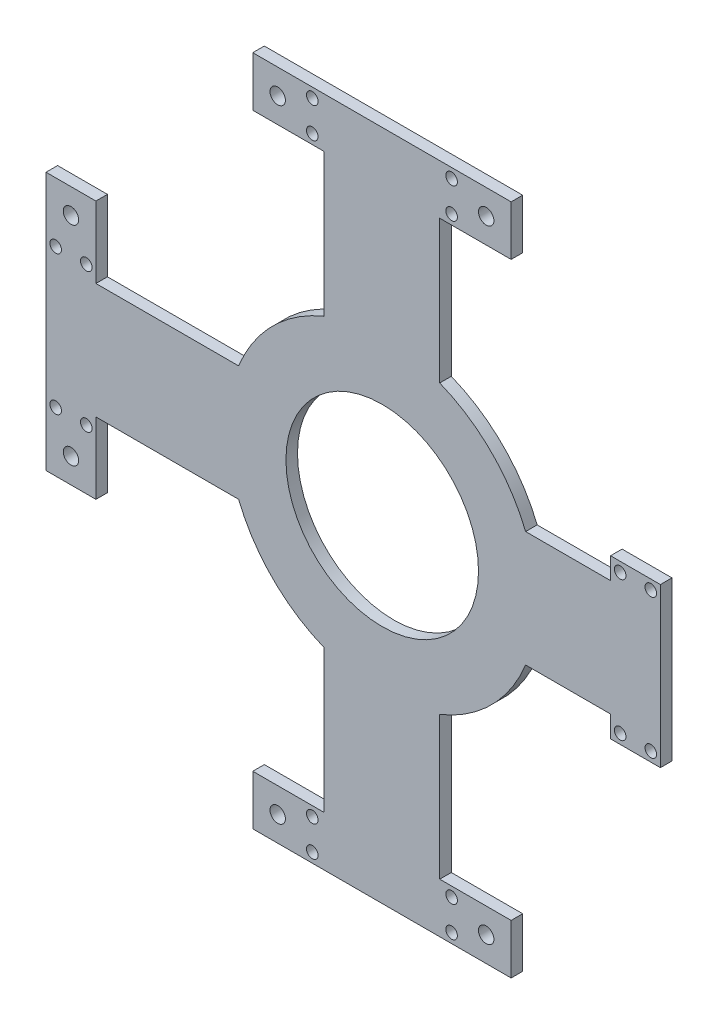
SolidWorks part; units mm, degrees
ref_plane "Alzado" through (0, 0, 0) normal (0, 0, 1) x (1, 0, 0)
ref_plane "Planta" through (0, 0, 0) normal (0, 1, 0) x (1, 0, 0)
ref_plane "Vista lateral" through (0, 0, 0) normal (1, 0, 0) x (0, 0, -1)
sketch "Croquis1" plane through (0, 0, 0) normal (0, 0, 1) x (1, 0, 0)
  line L0 (0, 0) -> (0, 37.2565) construction
  line L1 (-15.071, 74.3065) -> (-15.071, 37.2565)
  line L2 (-37.2851, 15) -> (-74.3351, 15)
  line L3 (-15.071, 37.2565) -> (14.929, 37.2565) construction
  line L4 (14.929, 37.2565) -> (14.929, 74.3065)
  line L5 (-15.071, 74.3065) -> (-20.661, 74.3065)
  line L6 (-25, 0) -> (25, 0) construction
  line L7 (0, 25) -> (0, -25) construction
  line L8 (-15.071, -37.2565) -> (-15.071, -74.3065)
  line L9 (14.929, -37.2565) -> (14.929, -74.3065)
  line L10 (14.929, 74.3065) -> (20.519, 74.3065)
  line L12 (-37.2851, -15) -> (-74.3351, -15)
  line L13 (-20.661, 74.3065) -> (-20.661, 87.2565)
  line L14 (-20.661, 87.2565) -> (20.519, 87.2565)
  line L15 (20.519, 87.2565) -> (20.519, 74.3065)
  line L16 (20.519, -87.2565) -> (20.519, -74.3065)
  line L17 (14.929, -74.3065) -> (20.519, -74.3065)
  line L18 (-20.661, -87.2565) -> (20.519, -87.2565)
  line L19 (-20.661, -74.3065) -> (-20.661, -87.2565)
  line L20 (-15.071, -74.3065) -> (-20.661, -74.3065)
  line L21 (-74.3351, -15) -> (-74.3351, -20.59)
  line L22 (-74.3351, -20.59) -> (-87.2851, -20.59)
  line L23 (-87.2851, -20.59) -> (-87.2851, 20.59)
  line L24 (-87.2851, 20.59) -> (-74.3351, 20.59)
  line L25 (-74.3351, 20.59) -> (-74.3351, 15)
  line L26 (37.228, 15) -> (59.278, 15)
  line L27 (37.228, -15) -> (59.278, -15)
  line L28 (59.278, -15) -> (59.278, -20.59)
  line L29 (59.278, -20.59) -> (72.228, -20.59)
  line L30 (72.228, -20.59) -> (72.228, 20.59)
  line L31 (72.228, 20.59) -> (59.278, 20.59)
  line L32 (59.278, 20.59) -> (59.278, 15)
  arc A0 (-15.071, 37.2565) -> (-37.2851, 15) centre (0, 0) ccw
  circle A1 centre (0, 0) radius 25
  arc A2 (-37.2851, -15) -> (-15.071, -37.2565) centre (0, 0) ccw
  arc A3 (14.929, 37.2565) -> (37.228, 15) centre (0, 0) cw
  arc A4 (14.929, -37.2565) -> (37.228, -15) centre (0, 0) ccw
  dimension "D1" = 50
  dimension "D2" = 5.59
  dimension "D3" = 37.05
  dimension "D4" = 5.59
  dimension "D5" = 12.95
  dimension "D6" = 37.05
  dimension "D7" = 37.05
  dimension "D8" = 5.59
  dimension "D9" = 5.59
  dimension "D10" = 12.95
  dimension "D11" = 37.05
  dimension "D12" = 37.05
  dimension "D13" = 22.05
  dimension "D14" = 5.59
  dimension "D15" = 22.05
  dimension "D16" = 5.59
  dimension "D17" = 12.95
  dimension "D18" = 12.95
  dimension "D19" = 30
  dimension "D20" = 12.95
  dimension "D21" = 41.18
extrude "Saliente-Extruir1" add sketch "Croquis1" along normal blind 3
sketch "Croquis2" plane through (0, 0, 0) normal (0, 0, -1) x (-1, 0, 0)
  line L1 (-20.519, 87.2565) -> (-33.469, 87.2565)
  line L2 (-20.519, 87.2565) -> (-20.519, 74.3065)
  line L3 (-20.519, 74.3065) -> (-33.469, 74.3065)
  line L4 (-33.469, 87.2565) -> (-33.469, 74.3065)
  line L5 (20.661, 87.2565) -> (33.611, 87.2565)
  line L6 (20.661, 87.2565) -> (20.661, 74.3065)
  line L7 (20.661, 74.3065) -> (33.611, 74.3065)
  line L8 (33.611, 87.2565) -> (33.611, 74.3065)
  line L9 (-20.519, -74.3065) -> (-33.469, -74.3065)
  line L10 (-20.519, -74.3065) -> (-20.519, -87.2565)
  line L11 (-20.519, -87.2565) -> (-33.469, -87.2565)
  line L12 (-33.469, -74.3065) -> (-33.469, -87.2565)
  line L13 (20.661, -74.3065) -> (33.611, -74.3065)
  line L14 (20.661, -74.3065) -> (20.661, -87.2565)
  line L15 (20.661, -87.2565) -> (33.611, -87.2565)
  line L16 (33.611, -74.3065) -> (33.611, -87.2565)
  line L17 (74.3351, 20.59) -> (87.2851, 20.59)
  line L18 (74.3351, 20.59) -> (74.3351, 33.54)
  line L19 (74.3351, 33.54) -> (87.2851, 33.54)
  line L20 (87.2851, 20.59) -> (87.2851, 33.54)
  line L21 (74.3351, -20.59) -> (87.2851, -20.59)
  line L22 (74.3351, -20.59) -> (74.3351, -33.54)
  line L23 (74.3351, -33.54) -> (87.2851, -33.54)
  line L24 (87.2851, -20.59) -> (87.2851, -33.54)
  dimension "D1" = 12.95
  dimension "D2" = 12.95
  dimension "D3" = 12.95
  dimension "D4" = 12.95
  dimension "D5" = 12.95
  dimension "D6" = 12.95
  dimension "D7" = 12.95
  dimension "D8" = 12.95
  dimension "D9" = 12.95
  dimension "D10" = 12.95
  dimension "D11" = 12.95
extrude "Saliente-Extruir2" add sketch "Croquis2" against normal blind 3
sketch "Croquis3" plane through (0, 0, 0) normal (0, 0, -1) x (-1, 0, 0)
  line L0 (-33.469, 74.3065) -> (-20.519, 74.3065) construction
  line L1 (-14.929, 74.3065) -> (-33.469, 74.3065) construction
  line L2 (-33.469, 74.3065) -> (-20.519, 87.2565) construction
  line L3 (33.611, 87.2565) -> (-33.469, 87.2565) construction
  line L4 (-20.519, -74.3065) -> (-20.519, -87.2565) construction
  line L5 (-14.929, -74.3065) -> (-33.469, -74.3065) construction
  line L6 (33.611, -87.2565) -> (-33.469, -87.2565) construction
  line L7 (33.611, 87.2565) -> (20.661, 87.2565) construction
  line L8 (20.661, 87.2565) -> (20.661, 74.3065) construction
  line L9 (15.071, 74.3065) -> (33.611, 74.3065) construction
  line L10 (33.611, -74.3065) -> (20.661, -74.3065) construction
  line L12 (-33.469, -74.3065) -> (-20.519, -87.2565) construction
  line L13 (15.071, -74.3065) -> (33.611, -74.3065) construction
  line L14 (20.661, 74.3065) -> (33.611, 74.3065) construction
  line L15 (33.611, 74.3065) -> (20.661, 87.2565) construction
  line L16 (87.2851, -33.54) -> (87.2851, -20.59) construction
  line L17 (87.2851, -33.54) -> (87.2851, 33.54) construction
  line L18 (87.2851, -20.59) -> (74.3351, -20.59) construction
  line L19 (74.3351, -15) -> (74.3351, -33.54) construction
  line L20 (87.2851, 33.54) -> (87.2851, 20.59) construction
  line L21 (87.2851, 20.59) -> (74.3351, 20.59) construction
  line L22 (74.3351, 33.54) -> (74.3351, 15) construction
  line L23 (87.2851, 20.59) -> (74.3351, 33.54) construction
  line L24 (74.3351, -33.54) -> (87.2851, -20.59) construction
  line L26 (-20.519, -74.3065) -> (-33.469, -74.3065) construction
  line L27 (-33.469, 87.2565) -> (-33.469, 74.3065) construction
  line L28 (33.611, 74.3065) -> (33.611, 87.2565) construction
  line L29 (87.2851, 33.54) -> (74.3351, 33.54) construction
  line L30 (74.3351, -33.54) -> (87.2851, -33.54) construction
  line L32 (-33.469, -74.3065) -> (-33.469, -87.2565) construction
  line L33 (20.661, -74.3065) -> (20.661, -87.2565) construction
  line L34 (20.661, -87.2565) -> (33.611, -74.3065) construction
  line L35 (33.611, -87.2565) -> (33.611, -74.3065) construction
  circle A0 centre (-26.994, 80.7815) radius 2
  circle A1 centre (27.136, 80.7815) radius 2
  circle A2 centre (27.136, -80.7815) radius 2
  circle A3 centre (-26.994, -80.7815) radius 2
  circle A4 centre (80.8101, -27.065) radius 2
  circle A5 centre (80.8101, 27.065) radius 2
  dimension "D1" = 4
  dimension "D2" = 4
  dimension "D3" = 4
  dimension "D4" = 4
  dimension "D5" = 4
  dimension "D6" = 4
  dimension "D7" = 6.475
  dimension "D8" = 6.475
  dimension "D9" = 6.475
  dimension "D10" = 6.475
  dimension "D11" = 6.475
  dimension "D12" = 6.475
extrude "Cortar-Extruir1" cut sketch "Croquis3" against normal through all
sketch "Croquis4" plane through (0, 0, 0) normal (0, 0, -1) x (-1, 0, 0)
  line L0 (25, 0) -> (-25, 0) construction
  line L1 (20.661, -87.2565) -> (20.661, -74.3065) construction
  line L2 (76.8351, -33.54) -> (76.8351, -18.09) construction
  line L3 (15.071, -74.3065) -> (33.611, -74.3065) construction
  line L4 (33.611, -87.2565) -> (-33.469, -87.2565) construction
  line L5 (20.661, -87.2565) -> (-20.519, -87.2565) construction
  line L6 (20.661, -74.3065) -> (-20.519, -74.3065) construction
  line L7 (-14.929, -74.3065) -> (-33.469, -74.3065) construction
  line L8 (-20.519, -74.3065) -> (-20.519, -87.2565) construction
  line L9 (74.3351, -33.54) -> (87.2851, -33.54) construction
  line L10 (76.8351, -18.09) -> (74.3351, -18.09) construction
  line L11 (74.3351, -15) -> (74.3351, -33.54) construction
  line L12 (80.8101, -33.54) -> (80.8101, 33.54) construction
  line L13 (87.2851, 33.54) -> (74.3351, 33.54) construction
  line L14 (0, 25) -> (0, -25) construction
  line L15 (-69.728, 18.09) -> (-61.778, 18.09) construction
  line L16 (-61.778, 18.09) -> (-61.778, -18.09) construction
  line L17 (-61.778, -18.09) -> (-69.728, -18.09) construction
  line L18 (-69.728, -18.09) -> (-69.728, 18.09) construction
  line L19 (-59.278, -15) -> (-59.278, -20.59) construction
  line L22 (-72.228, 20.59) -> (-59.278, 20.59) construction
  line L23 (-59.278, -20.59) -> (-72.228, -20.59) construction
  line L24 (-33.469, 87.2565) -> (-33.469, 74.3065) construction
  circle A0 centre (0, 0) radius 25 construction
  circle A1 centre (-18.019, -84.7565) radius 1.5
  circle A2 centre (-18.019, -76.8065) radius 1.5
  circle A3 centre (18.161, -76.8065) radius 1.5
  circle A4 centre (18.161, -84.7565) radius 1.5
  circle A5 centre (18.161, 76.8065) radius 1.5
  circle A6 centre (18.161, 84.7565) radius 1.5
  circle A7 centre (-18.019, 84.7565) radius 1.5
  circle A8 centre (-18.019, 76.8065) radius 1.5
  circle A9 centre (76.8351, -18.09) radius 1.5
  circle A10 centre (84.7851, -18.09) radius 1.5
  circle A11 centre (76.8351, 18.09) radius 1.5
  circle A12 centre (84.7851, 18.09) radius 1.5
  circle A13 centre (-69.728, -18.09) radius 1.5
  circle A14 centre (-61.778, -18.09) radius 1.5
  circle A15 centre (-69.728, 18.09) radius 1.5
  circle A16 centre (-61.778, 18.09) radius 1.5
  dimension "D1" = 3
  dimension "D2" = 3
  dimension "D3" = 3
  dimension "D4" = 3
  dimension "D5" = 2.5
  dimension "D6" = 2.5
  dimension "D7" = 2.5
  dimension "D8" = 2.5
  dimension "D9" = 2.5
  dimension "D10" = 2.5
  dimension "D13" = 2.5
  dimension "D14" = 15.45
  dimension "D16" = 3
  dimension "D17" = 3
  dimension "D18" = 3
  dimension "D19" = 3
  dimension "D20" = 3
  dimension "D22" = 2.5
  dimension "D23" = 2.5
  dimension "D24" = 2.5
  dimension "D25" = 15.45
  dimension "D11" = 41.18
  dimension "D12" = 2.5
  dimension "D15" = 2.5
  dimension "D21" = 7.95
extrude "Cortar-Extruir2" cut sketch "Croquis4" against normal through all
